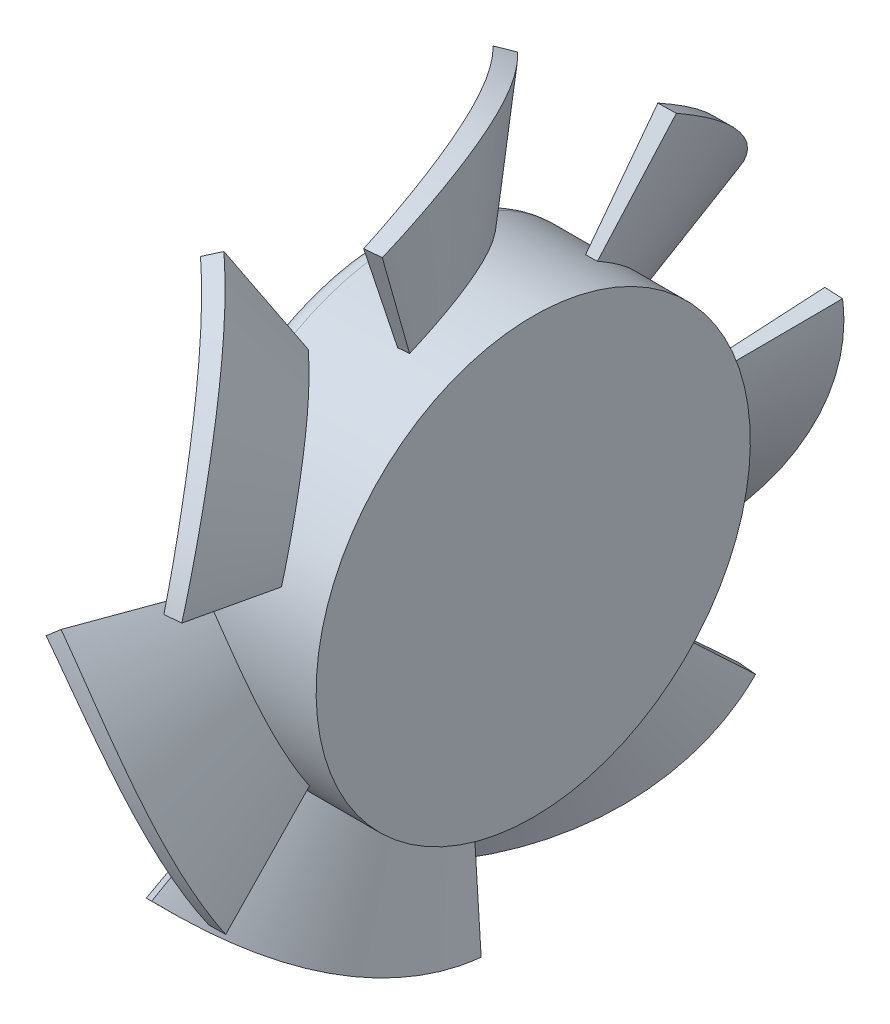
SolidWorks part; units mm, degrees
material "PW100:Mi:0:30:C1:0:1:2:Re:16:"
ref_plane "Front" through (0, 0, 0) normal (0, 0, 1) x (1, 0, 0)
ref_plane "Top" through (0, 0, 0) normal (0, 1, 0) x (1, 0, 0)
ref_plane "Right" through (0, 0, 0) normal (1, 0, 0) x (0, 0, -1)
sketch "Support-Front" plane through (0, 0, 0) normal (0, 0, 1) x (1, 0, 0)
  line L0 (-10, 0) -> (-2, 0) construction
  line L1 (-10, -11.5) -> (-10, 11.5)
  line L2 (-10, 11.5) -> (-2, 11.5)
  line L3 (-10, -11.5) -> (-2, -11.5)
  line L4 (-2, 11.5) -> (-2, -11.5)
  line L5 (-6, 11.5) -> (-6, -11.5) construction
  line L6 (-2, 11.5) -> (0, 11.5) construction
  line L7 (-2, -11.5) -> (0, -11.5) construction
  line L8 (0, 11.5) -> (0, -11.5) construction
  line L11 (-6, 11.5) -> (-6, 18) construction
  line L12 (-6, -11.5) -> (-6, -18) construction
  point P12 (0, 0)
  point P14 (-6, 0)
  dimension "Width" = 10
  dimension "Diam-Body" = 23
  dimension "Diam-Fan" = 36
  dimension "Dist-Fan" = 2
sketch "Support-Right" plane through (0, 0, 0) normal (1, 0, 0) x (0, 0, -1)
  circle A0 centre (0, 0) radius 18
sketch "Support-Fan-Blade-Top" plane through (0, 0, 0) normal (0, 1, 0) x (-1, 0, 0)
  line L0 (6, 0) -> (4.2205, 7.137) construction
  line L1 (10.1132, -6.098) -> (4.2205, 7.137) construction
  line L2 (7.1668, 0.5195) -> (6, 0) construction
  line L4 (10, 0) -> (4.2205, 7.137) construction
  line L5 (10, 0) -> (2, 0) construction
  line L6 (3.223, 7.0673) -> (4.2205, 7.137)
  line L7 (9.3938, -6.7927) -> (10.1132, -6.098)
  arc A0 (4.2205, 7.137) -> (10.1132, -6.098) centre (25.3484, 8.6144) ccw
  arc A1 (3.223, 7.0673) -> (9.3938, -6.7927) centre (25.3484, 8.6144) ccw
  dimension "Angle-Fan-Blade" = 66
  dimension "D1" = 10
  dimension "D3" = 51
  dimension "D2" = 1
ref_plane "Plane-Angle-Fan-Blade" through (-5.0074, 0, 2.2294) normal (-0.9135, 0, 0.4067) x (0.4067, 0, 0.9135)
ref_plane "Plane-Top-Fan-Blade" through (0, 18, 0) normal (0, 1, 0) x (-1, 0, 0)
sketch "Sketch-Blade-Bottom" plane through (0, 0, 0) normal (0, 1, 0) x (1, 0, 0)
  point P0 (-6, 0)
sketch "Sketch-Blade-Top" plane through (0, 18, 0) normal (0, 1, 0) x (-1, 0, 0)
  line L2 (4.2205, 7.137) -> (3.223, 7.0673)
  line L3 (9.3938, -6.7927) -> (10.1132, -6.098)
  line L4 (4.2205, 7.137) -> (3.223, 7.0673)
  line L5 (9.3938, -6.7927) -> (10.1132, -6.098)
  arc A3 (3.223, 7.0673) -> (9.3938, -6.7927) centre (25.3484, 8.6144) ccw
  arc A4 (4.2205, 7.137) -> (10.1132, -6.098) centre (25.3484, 8.6144) ccw
  arc A5 (3.223, 7.0673) -> (9.3938, -6.7927) centre (25.3484, 8.6144) ccw
  arc A6 (4.2205, 7.137) -> (10.1132, -6.098) centre (25.3484, 8.6144) ccw
  dimension "D1" = 0
sketch "Sketch5" plane through (0, 0, 0) normal (0, 0, 1) x (1, 0, 0)
  line L0 (-2, 11.5) -> (-2, -11.5) construction
  line L1 (-10, -11.5) -> (-10, 11.5) construction
  line L4 (-2, 11.5) -> (-2, 0)
  line L5 (-10, 0) -> (-10, 11.5)
  line L6 (-10, 0) -> (-2, 0)
  line L7 (-10, 11.5) -> (-2, 11.5) construction
  line L8 (-10, 0) -> (-2, 0) construction
  line L9 (-10, 0) -> (-2, 0) construction
  line L10 (-10, 11.5) -> (-2, 11.5)
revolve "Body" add sketch "Sketch5" angle 360 about L9
loft "Loft-Fan-Blade" add profiles "Sketch-Blade-Top", "Sketch-Blade-Bottom"
pattern_circular "CirPattern1" count 7 over 360 about axis through (-10, 0, 0) along (1, 0, 0) of "Loft-Fan-Blade"
sketch "Sketch-Cut-Blade" plane through (0, 0, 0) normal (1, 0, 0) x (0, 0, -1)
  circle A0 centre (0, 0) radius 18 construction
  circle A1 centre (0, 0) radius 18
extrude "Cut-Fan-Blade" cut sketch "Sketch-Cut-Blade" against normal through all flip side to cut
fillet "Cosmetic-Fillet" radius 1 1 edges at (-10, -11.5, 0)
equation "\"Angle-Blade@Plane-Angle-Fan-Blade\" = \"Angle-Fan-Blade@Support-Fan-Blade-Top\""
equation "\"Rad@Cosmetic-Fillet\" = \"Dist-Fan@Support-Front\"/2"
